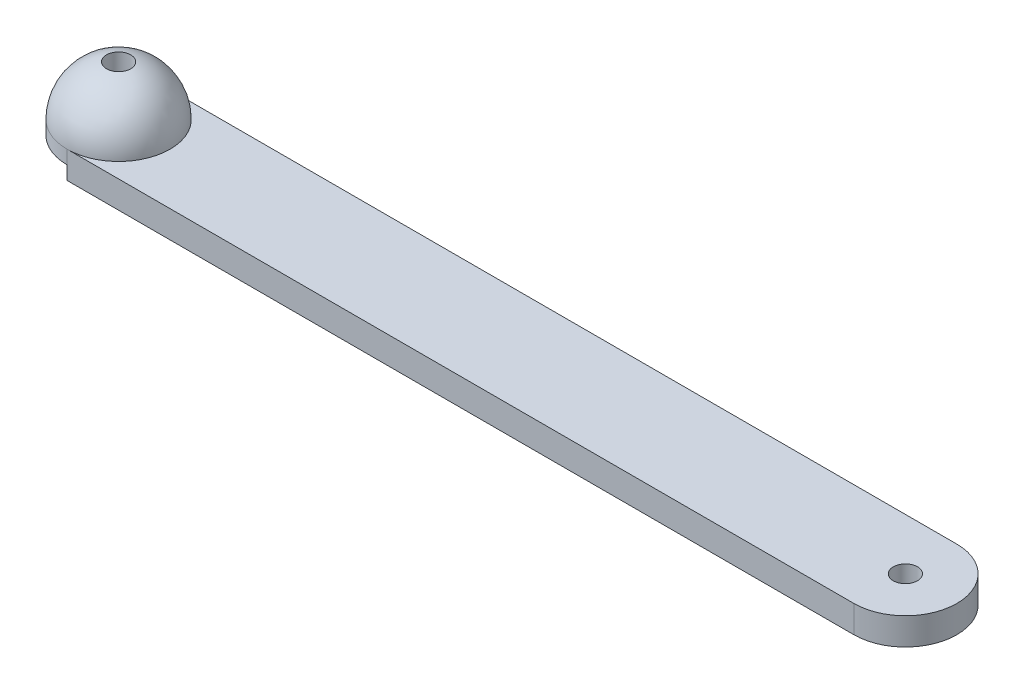
SolidWorks part; units mm, degrees
ref_plane "Plan de face" through (0, 0, 0) normal (0, 0, 1) x (1, 0, 0)
ref_plane "Plan de dessus" through (0, 0, 0) normal (0, 1, 0) x (1, 0, 0)
ref_plane "Plan de droite" through (0, 0, 0) normal (1, 0, 0) x (0, 0, -1)
sketch "Esquisse1" plane through (0, 0, 0) normal (0, 1, 0) x (1, 0, 0)
  line L0 (-232.15, 0) -> (232.15, 0) construction
  line L1 (-232.15, 30.35) -> (232.15, 30.35)
  line L2 (-232.15, -30.35) -> (232.15, -30.35)
  arc A0 (-232.15, 30.35) -> (-232.15, -30.35) centre (-232.15, 0) ccw
  arc A1 (232.15, -30.35) -> (232.15, 30.35) centre (232.15, 0) ccw
  point P2 (0, 0)
  dimension "D1" = 464.3
  dimension "D2" = 60.7
extrude "Boss.-Extru.1" add sketch "Esquisse1" along normal mid plane 16
sketch "Esquisse2" plane through (0, 8, 0) normal (0, 1, 0) x (1, 0, 0)
  circle A0 centre (232.15, 0) radius 7.15
  dimension "D1" = 14.3
extrude "Enlèv. mat.-Extru.1" cut sketch "Esquisse2" against normal through all
sketch "Esquisse3" plane through (0, 8, 0) normal (0, 1, 0) x (1, 0, 0)
  line L0 (232.15, 30.35) -> (-232.15, 30.35) construction
  line L1 (-232.15, 30.35) -> (-232.15, -30.35)
  arc A0 (-232.15, -30.35) -> (-232.15, 30.35) centre (-232.15, 0) cw
revolve "Révolution1" add sketch "Esquisse3" angle 180 about L1
sketch "Esquisse4" plane through (0, -8, 0) normal (0, -1, 0) x (1, 0, 0)
  circle A0 centre (-232.15, 0) radius 7.15
  dimension "D1" = 14.3
extrude "Enlèv. mat.-Extru.2" cut sketch "Esquisse4" against normal through all
sketch "Esquisse5" plane through (0, 0, 0) normal (0, 1, 0) x (1, 0, 0)
  circle A0 centre (-232.15, 0) radius 30.35
  dimension "D1" = 60.7
extrude "Enlèv. mat.-Extru.6" cut sketch "Esquisse5" along normal blind 8 from surface at -8 starting at face at (-232.15, -8, -7.15)
